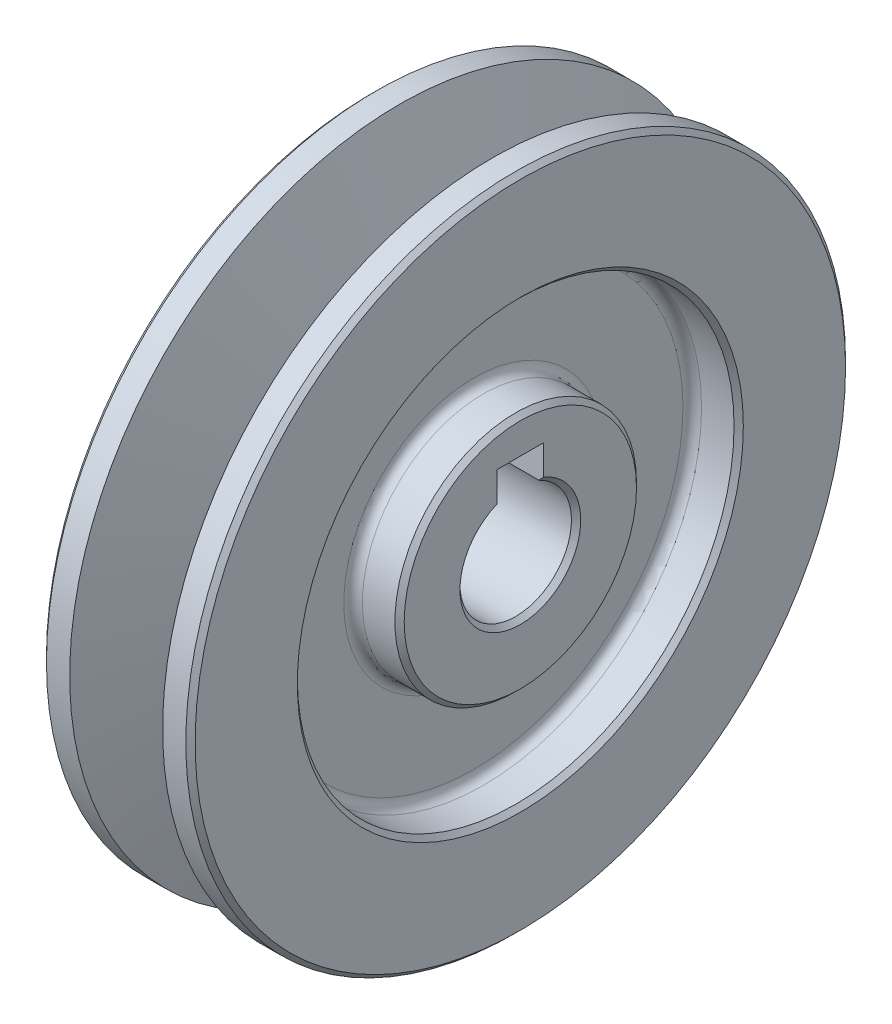
SolidWorks part; units mm, degrees
ref_plane "Front Plane" through (0, 0, 0) normal (0, 0, 1) x (1, 0, 0)
ref_plane "Top Plane" through (0, 0, 0) normal (0, 1, 0) x (1, 0, 0)
ref_plane "Right Plane" through (0, 0, 0) normal (1, 0, 0) x (0, 0, -1)
sketch "Sketch1" plane through (0, 0, 0) normal (0, 1, 0) x (1, 0, 0)
  line L0 (-8, 35.5) -> (-8, 23.5)
  line L1 (-8, 35.5) -> (-5, 35.5)
  line L2 (8, 35.5) -> (8, 23.5)
  line L3 (8, 23.5) -> (3, 23.5)
  line L4 (3, 23.5) -> (3, 13)
  line L5 (3, 13) -> (8, 13)
  line L6 (8, 13) -> (8, 6)
  line L7 (8, 6) -> (-8, 6)
  line L8 (-8, 6) -> (-8, 13)
  line L9 (-8, 13) -> (-3, 13)
  line L10 (-3, 13) -> (-3, 23.5)
  line L11 (-3, 23.5) -> (-8, 23.5)
  line L12 (0, 0) -> (0, 25.5) construction
  line L13 (-5, 35.5) -> (-1.9427, 25.5)
  line L14 (-1.9427, 25.5) -> (1.9427, 25.5)
  line L15 (1.9427, 25.5) -> (5, 35.5)
  line L16 (5, 35.5) -> (8, 35.5)
  line L17 (0, 0) -> (-42.3045, 0) construction
  point P22 (0, 25.5)
  point P23 (0, 6)
  dimension "D1" = 10
  dimension "D2" = 10
  dimension "D3" = 34
  dimension "D4" = 16
  dimension "D5" = 16
  dimension "D6" = 5
  dimension "D7" = 7
  dimension "D8" = 6
  dimension "D9" = 35.5
  dimension "D10" = 12
revolve "Revolve1" add sketch "Sketch1" angle 360 about L17
chamfer "Chamfer1" distance 0.5 angle 45 3 edges at (8, 0, -6) (8, 0, -13) (8, 0, -35.5)
chamfer "Chamfer2" distance 0.5 angle 45 4 edges at (-8, 0, -13) (-8, 0, -6) (-8, 0, -35.5) (-8, 0, -23.5)
fillet "Fillet2" radius 1 2 edges at (-3, 0, -23.5) (-3, 0, -13)
sketch "Sketch2" plane through (8, 0, 0) normal (1, 0, 0) x (0, 0, -1)
  line L0 (-2.5, 9.2) -> (-2.5, 4.6895)
  line L1 (-2.5, 9.2) -> (2.5, 9.2)
  line L4 (2.5, 9.2) -> (2.5, 6)
  line L7 (-2.5, 4.6895) -> (2.5, 4.6895)
  line L8 (2.5, 4.6895) -> (2.5, 6)
  point P0 (0, 17.82)
  point P5 (0, 4.6895)
  dimension "D1" = 3.2
  dimension "D2" = 5
  dimension "D3" = 9.2
extrude "Cut-Extrude1" cut sketch "Sketch2" against normal through all
fillet "Fillet3" radius 1 2 edges at (3, 0, -13) (3, 0, -23.5)
chamfer "Chamfer3" distance 0.5 angle 45 1 edges at (8, 0, -23.5)
